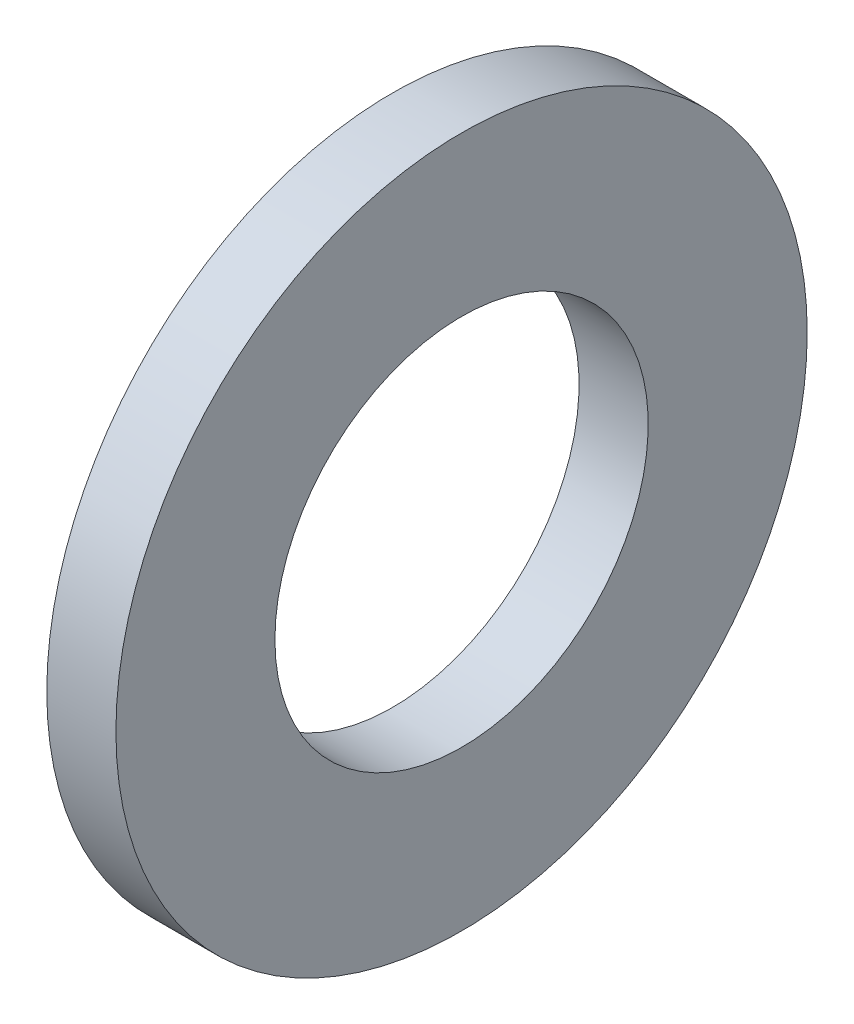
SolidWorks part; units mm, degrees
ref_plane "Plane1" through (0, 0, 0) normal (0, 0, 1) x (1, 0, 0)
ref_plane "Plane2" through (0, 0, 0) normal (0, 1, 0) x (1, 0, 0)
ref_plane "Plane3" through (0, 0, 0) normal (1, 0, 0) x (0, 0, -1)
sketch "Sketch1" plane through (0, 0, 0) normal (0, 0, 1) x (1, 0, 0)
  line L0 (-34.925, 0) -> (9.525, 0) construction
  line L1 (0, 1.35) -> (0, 2.5)
  line L2 (0, 2.5) -> (-0.5, 2.5)
  line L3 (-0.5, 2.5) -> (-0.5, 1.35)
  line L4 (-0.5, 1.35) -> (0, 1.35)
  dimension "Thickness" = 0.5
  dimension "Inside_dia" = 2.7
  dimension "Outside_dia" = 5
revolve "Base-Revolve" add sketch "Sketch1" angle 360 about L0
